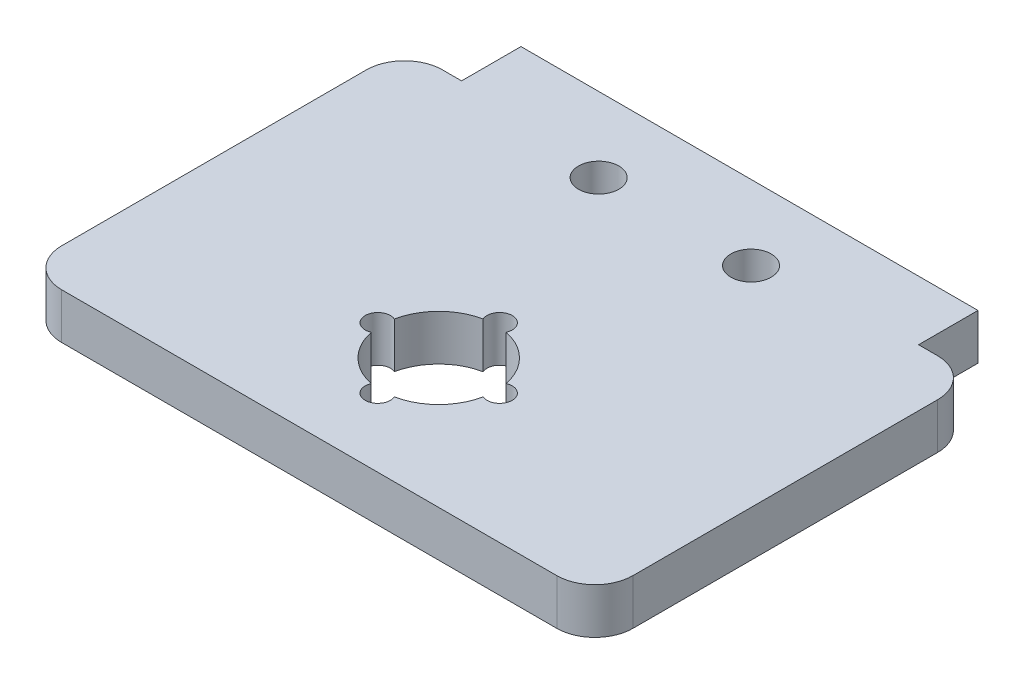
SolidWorks part; units mm, degrees
ref_plane "前视基准面" through (0, 0, 0) normal (0, 0, 1) x (1, 0, 0)
ref_plane "上视基准面" through (0, 0, 0) normal (0, 1, 0) x (1, 0, 0)
ref_plane "右视基准面" through (0, 0, 0) normal (1, 0, 0) x (0, 0, -1)
sketch "草图1" plane through (0, 0, 0) normal (0, 1, 0) x (1, 0, 0)
  line L0 (0, 80.2608) -> (0, -70.9317) construction
  line L1 (-25, 80.2608) -> (-25, -70.9317) construction
  line L2 (25, 80.2608) -> (25, -70.9317) construction
  line L3 (-49.3571, 0) -> (56.9138, 0) construction
  line L4 (-33.4853, 8.4853) -> (-16.5147, 8.4853) construction
  line L5 (-37.5, 28) -> (-37.5, -12)
  line L6 (37.5, 28) -> (37.5, -12)
  line L7 (-32.5, -17) -> (32.5, -17)
  line L8 (-49.3571, 13) -> (56.9138, 13) construction
  line L9 (-30, 33) -> (-30, 42.8002)
  line L10 (-20, 80.2608) -> (-20, 42.8002) construction
  line L11 (20, 80.2608) -> (20, -70.9317) construction
  line L12 (-32.5, 33) -> (-30, 33)
  line L13 (-37.5, 80.2608) -> (-37.5, -70.9317) construction
  line L14 (-49.3571, -17) -> (56.9138, -17) construction
  line L15 (37.5, 80.2608) -> (37.5, -70.9317) construction
  line L16 (-30, 42.8002) -> (30, 42.8002)
  line L17 (-30, 80.2608) -> (-30, 33) construction
  line L18 (30, 80.2608) -> (30, 33) construction
  line L20 (30, 13) -> (37.5, 13)
  line L22 (-30, 13) -> (-37.5, 13)
  line L23 (30, 42.8002) -> (30, 33)
  line L24 (-11.7385, 33) -> (-8.2615, 33)
  line L25 (-20, 33) -> (-20, -70.9317) construction
  line L26 (-20, 80.2608) -> (-20, -70.9317) construction
  line L27 (8.2615, 33) -> (11.7385, 33)
  line L28 (30, 33) -> (32.5, 33)
  line L29 (30, 13) -> (30, -70.9317) construction
  line L30 (30, 80.2608) -> (30, -70.9317) construction
  line L31 (-30, 13) -> (-30, -70.9317) construction
  line L32 (-30, 80.2608) -> (-30, -70.9317) construction
  circle A1 centre (-25, 0) radius 12 construction
  circle A11 centre (0, 0) radius 7.5
  circle A12 centre (0, 0) radius 8 construction
  circle A13 centre (0, 0) radius 11 construction
  circle A14 centre (0, 8) radius 1.65
  circle A15 centre (8, 0) radius 1.65
  circle A16 centre (0, -8) radius 1.65
  circle A17 centre (-8, 0) radius 1.65
  arc A21 (-37.5, -12) -> (-32.5, -17) centre (-32.5, -12) ccw
  arc A22 (32.5, -17) -> (37.5, -12) centre (32.5, -12) ccw
  arc A23 (37.5, 28) -> (32.5, 33) centre (32.5, 28) ccw
  arc A24 (-32.5, 33) -> (-37.5, 28) centre (-32.5, 28) ccw
  circle A25 centre (-10, 31) radius 2.65
  circle A26 centre (10, 31) radius 2.65
  point P23 (-25, 0)
  point P50 (0, 0)
  dimension "D3" = 5.3
  dimension "D4" = 24
  dimension "D5" = 10
  dimension "D9" = 15
  dimension "D10" = 16
  dimension "D11" = 22
  dimension "D12" = 3.3
  dimension "D22" = 5
  dimension "D1" = 25
  dimension "D7" = 12.5
  dimension "D14" = 50
  dimension "D6" = 2
  dimension "D2" = 25
  dimension "D8" = 12.5
  dimension "D15" = 13
  dimension "D17" = 20
  dimension "D18" = 20
  dimension "D23" = 30
  dimension "D24" = 30
  dimension "D13" = 4
extrude "凸台-拉伸1" add sketch "草图1" along normal blind 6
sketch "草图2" plane through (0, 6, 0) normal (0, 1, 0) x (1, 0, 0)
  line L1 (-30, 42.8002) -> (30, 42.8002)
  line L2 (-30, 42.8002) -> (-30, 40.8002)
  line L3 (-30, 40.8002) -> (30, 40.8002)
  line L4 (30, 42.8002) -> (30, 40.8002)
  dimension "D1" = 2
extrude "切除-拉伸1" cut sketch "草图2" against normal blind 10
